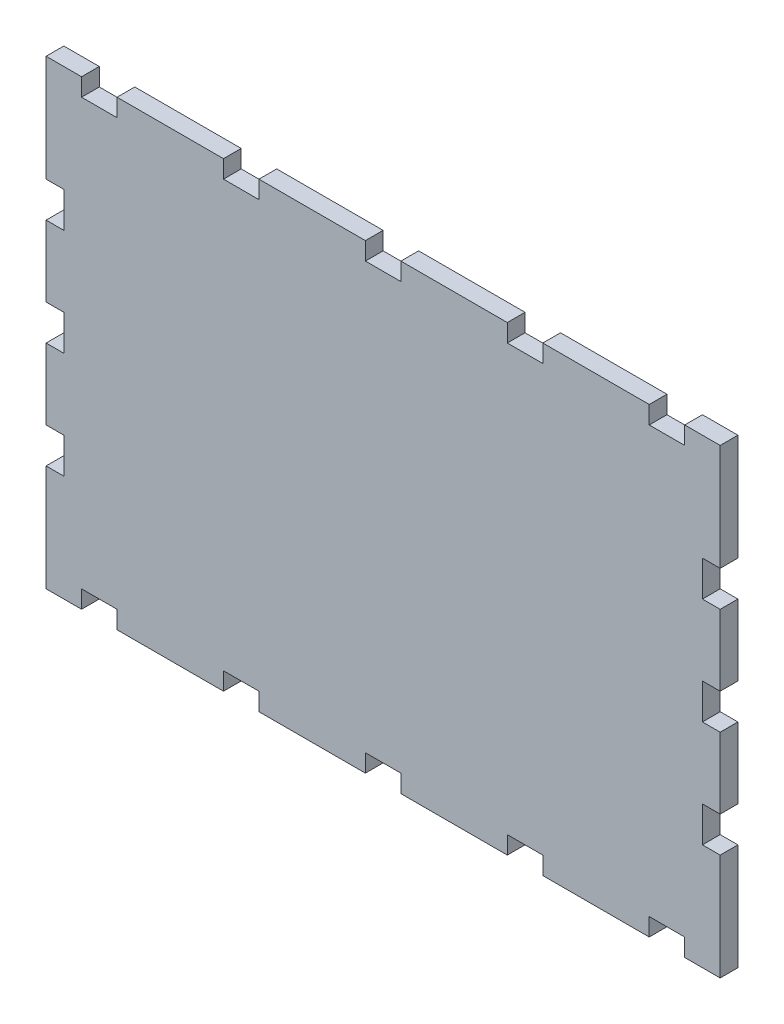
SolidWorks part; units mm, degrees
ref_plane "Ön Düzlem" through (0, 0, 0) normal (0, 0, 1) x (1, 0, 0)
ref_plane "Üst Düzlem" through (0, 0, 0) normal (0, 1, 0) x (1, 0, 0)
ref_plane "Sağ Düzlem" through (0, 0, 0) normal (1, 0, 0) x (0, 0, -1)
sketch "Sketch1" plane through (0, 0, 0) normal (0, 0, 1) x (1, 0, 0)
  line L0 (-85, 65) -> (-85, 60)
  line L1 (-95, -65) -> (-85, -65)
  line L2 (-95, -65) -> (-95, -35)
  line L3 (-95, 65) -> (-85, 65)
  line L4 (95, -65) -> (95, -35)
  line L5 (-95, -65) -> (95, 65) construction
  line L6 (-95, 65) -> (95, -65) construction
  line L7 (-85, 60) -> (-75, 60)
  line L8 (-75, 60) -> (-75, 65)
  line L10 (-5, 65) -> (-5, -55) construction
  line L11 (-85, -65) -> (-85, -60)
  line L12 (-85, -60) -> (-75, -60)
  line L13 (-75, -60) -> (-75, -65)
  line L14 (-45, 65) -> (-45, 60)
  line L15 (-35, 60) -> (-35, 65)
  line L16 (-45, 60) -> (-35, 60)
  line L17 (-45, -60) -> (-35, -60)
  line L18 (-45, -65) -> (-45, -60)
  line L19 (-35, -60) -> (-35, -65)
  line L20 (-5, 65) -> (-5, 60)
  line L21 (5, 60) -> (5, 65)
  line L22 (-5, 60) -> (5, 60)
  line L23 (-5, -60) -> (5, -60)
  line L24 (-5, -65) -> (-5, -60)
  line L25 (5, -60) -> (5, -65)
  line L26 (35, 65) -> (35, 60)
  line L27 (45, 60) -> (45, 65)
  line L28 (35, 60) -> (45, 60)
  line L29 (35, -60) -> (45, -60)
  line L30 (35, -65) -> (35, -60)
  line L31 (45, -60) -> (45, -65)
  line L32 (75, 65) -> (75, 60)
  line L33 (85, 60) -> (85, 65)
  line L34 (75, 60) -> (85, 60)
  line L35 (75, -60) -> (85, -60)
  line L36 (75, -65) -> (75, -60)
  line L37 (85, -60) -> (85, -65)
  line L38 (-75, -65) -> (-45, -65)
  line L39 (-35, -65) -> (-5, -65)
  line L40 (5, -65) -> (35, -65)
  line L41 (45, -65) -> (75, -65)
  line L42 (85, -65) -> (95, -65)
  line L43 (85, 65) -> (95, 65)
  line L44 (115, -60) -> (125, -60) [skipped]
  line L45 (115, -65) -> (115, -60) [skipped]
  line L46 (125, -60) -> (125, -65) [skipped]
  line L47 (115, 65) -> (115, 60) [skipped]
  line L48 (125, 60) -> (125, 65) [skipped]
  line L49 (115, 60) -> (125, 60) [skipped]
  line L50 (45, 65) -> (75, 65)
  line L51 (5, 65) -> (35, 65)
  line L52 (-35, 65) -> (-5, 65)
  line L53 (-75, 65) -> (-45, 65)
  line L54 (-95, 35) -> (-90, 35)
  line L55 (-90, 35) -> (-90, 25)
  line L56 (-90, 25) -> (-95, 25)
  line L57 (90, 25) -> (95, 25)
  line L58 (90, 35) -> (90, 25)
  line L59 (95, 35) -> (90, 35)
  line L60 (-95, 5) -> (-90, 5)
  line L61 (-90, 5) -> (-90, -5)
  line L62 (-90, -5) -> (-95, -5)
  line L63 (95, 5) -> (90, 5)
  line L64 (90, 5) -> (90, -5)
  line L65 (90, -5) -> (95, -5)
  line L66 (-95, -25) -> (-90, -25)
  line L67 (-90, -25) -> (-90, -35)
  line L68 (-90, -35) -> (-95, -35)
  line L69 (95, -25) -> (90, -25)
  line L70 (90, -25) -> (90, -35)
  line L71 (90, -35) -> (95, -35)
  line L72 (-95, 35) -> (-95, 65)
  line L73 (-95, 5) -> (-95, 25)
  line L74 (-95, -25) -> (-95, -5)
  line L75 (95, -25) -> (95, -5)
  line L76 (95, 5) -> (95, 25)
  line L77 (95, 35) -> (95, 65)
  point P0 (0, 0)
  dimension "D1" = 190
  dimension "D2" = 130
  dimension "D3" = 10
  dimension "D4" = 5
  dimension "D5" = 10
  dimension "D7" = 30
  dimension "D8" = 5
  dimension "D9" = 10
  dimension "D10" = 30
  dimension "D12" = 5
  dimension "D13" = 30
  dimension "D14" = 20
  dimension "D15" = 20
  dimension "D6" = 6
  dimension "D11" = 3
extrude "Boss-Extrude1" add sketch "Sketch1" along normal blind 5
